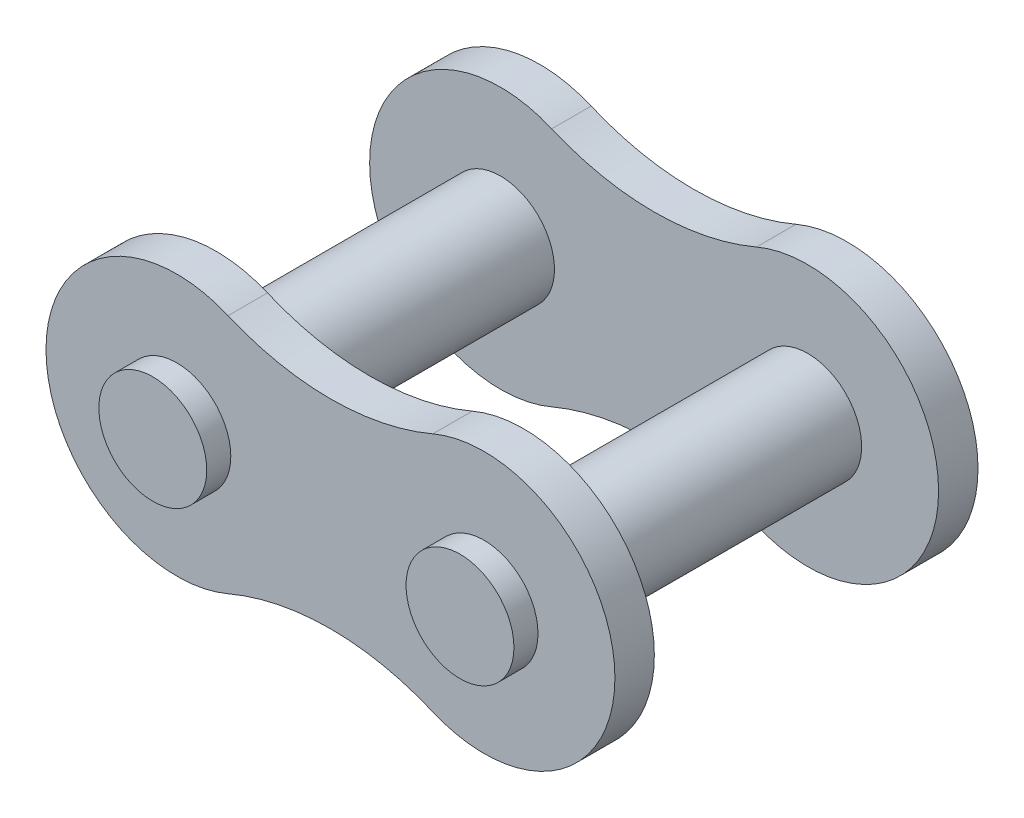
SolidWorks part; units mm, degrees
material "1.7033 (34Cr4)"
ref_plane "Спереди" through (0, 0, 0) normal (0, 0, 1) x (1, 0, 0)
ref_plane "Сверху" through (0, 0, 0) normal (0, 1, 0) x (1, 0, 0)
ref_plane "Справа" through (0, 0, 0) normal (1, 0, 0) x (0, 0, -1)
sketch "Эскиз1" plane through (0, 0, 0) normal (0, 0, 1) x (1, 0, 0)
  line L0 (-19.1742, 0) -> (12.4304, 0) construction
  line L1 (0, 6.9982) -> (0, -8.5377) construction
  circle A0 centre (-6.35, 0) radius 2.23
  circle A1 centre (6.35, 0) radius 2.23
  dimension "D1" = 12.7
  dimension "D2" = 4.46
extrude "Бобышка-Вытянуть1" add sketch "Эскиз1" along normal mid plane 17
sketch "Эскиз2" plane through (0, 0, 0) normal (0, 0, 1) x (1, 0, 0)
  arc A0 (-4.232, 4.9782) -> (-4.232, -4.9782) centre (-6.35, 0) ccw
  arc A1 (4.232, -4.9782) -> (4.232, 4.9782) centre (6.35, 0) ccw
  arc A2 (-4.232, 4.9782) -> (4.232, 4.9782) centre (0, 14.9253) ccw
  arc A3 (4.232, -4.9782) -> (-4.232, -4.9782) centre (0, -14.9253) ccw
  dimension "D1" = 10.82
  dimension "D2" = 21.62
extrude "Бобышка-Вытянуть2" add sketch "Эскиз2" along normal blind 1.63 from offset 5.875
mirror "Зеркальное отражение1" about plane through (0, 0, 0) normal (0, 0, 1) of "Бобышка-Вытянуть2"
